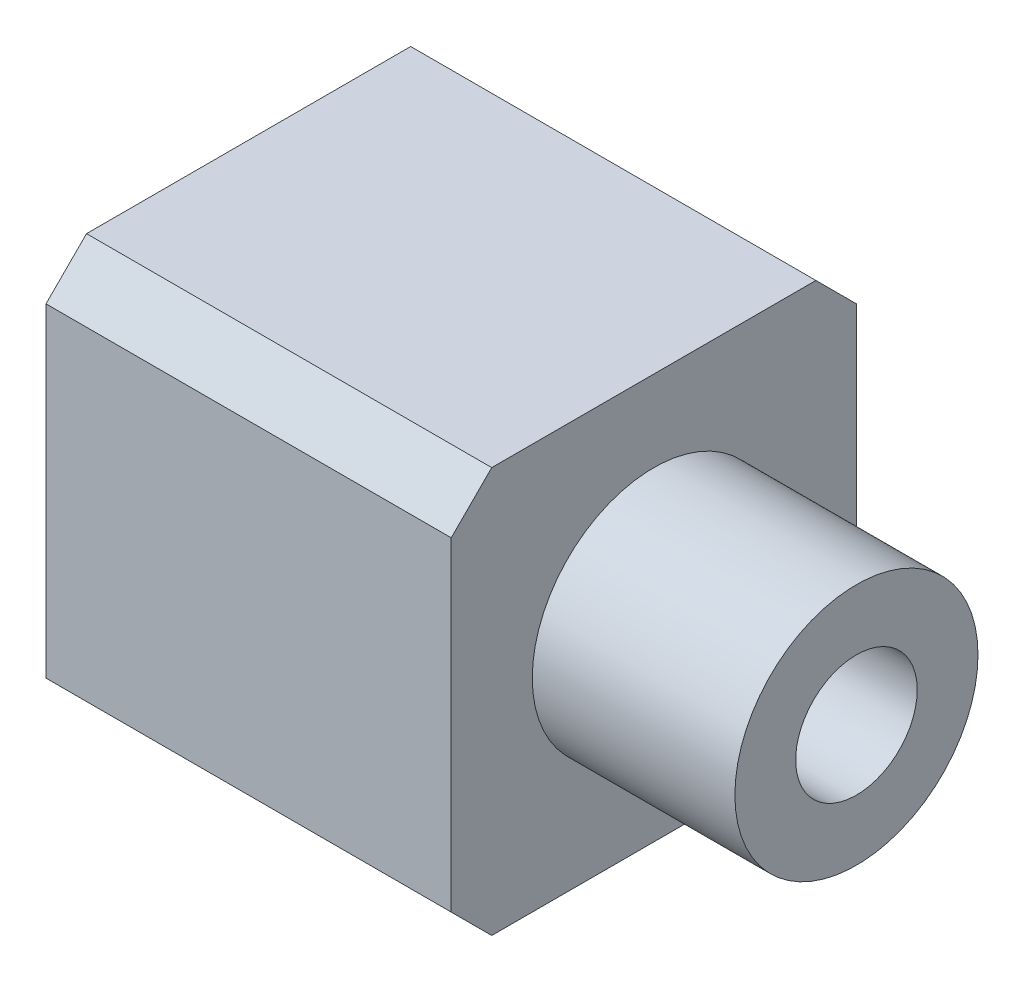
SolidWorks part; units mm, degrees
ref_plane "Front Plane" through (0, 0, 0) normal (0, 0, 1) x (1, 0, 0)
ref_plane "Top Plane" through (0, 0, 0) normal (0, 1, 0) x (1, 0, 0)
ref_plane "Right Plane" through (0, 0, 0) normal (1, 0, 0) x (0, 0, -1)
sketch "Sketch1" plane through (0, 0, 0) normal (1, 0, 0) x (0, 0, -1)
  line L5 (5, -5) -> (-5, -5)
  line L6 (5, -5) -> (5, 5)
  line L7 (5, 5) -> (-5, 5)
  line L8 (-5, -5) -> (-5, 5)
  line L9 (5, -5) -> (-5, 5) construction
  line L10 (5, 5) -> (-5, -5) construction
  point P0 (0, 0)
  dimension "D1" = 10
  dimension "D2" = 10
extrude "Boss-Extrude1" add sketch "Sketch1" against normal blind 17
sketch "Sketch2" plane through (0, 0, 0) normal (1, 0, 0) x (0, 0, -1)
  circle A0 centre (0, 0) radius 3
  circle A1 centre (0, 0) radius 15.3536
  dimension "D1" = 6
extrude "Cut-Extrude1" cut sketch "Sketch2" against normal blind 5
sketch "Sketch3" plane through (-17, 0, 0) normal (-1, 0, 0) x (0, 0, 1)
  circle A0 centre (0, 0) radius 3
  circle A1 centre (0, 0) radius 15.6354
  dimension "D1" = 6
extrude "Cut-Extrude2" cut sketch "Sketch3" against normal blind 2
sketch "Sketch4" plane through (0, 0, 0) normal (1, 0, 0) x (0, 0, -1)
  circle A0 centre (0, 0) radius 1.5
  dimension "D1" = 3
extrude "Cut-Extrude3" cut sketch "Sketch4" against normal through all
chamfer "Chamfer1" distance 1 angle 45 4 edges at (-10, -5, -5) (-10, 5, 5) (-10, -5, 5) (-10, 5, -5)
sketch "Sketch5" plane through (0, 0, 0) normal (0, 0, -1) x (-1, 0, 0)
  line L0 (0, 0) -> (10, 0) construction
  line L1 (0, 3) -> (0, -3) construction
  circle A0 centre (10, 0) radius 1.5
  dimension "D1" = 3
  dimension "D2" = 10
extrude "Cut-Extrude4" cut sketch "Sketch5" against normal blind 2 from offset 5
